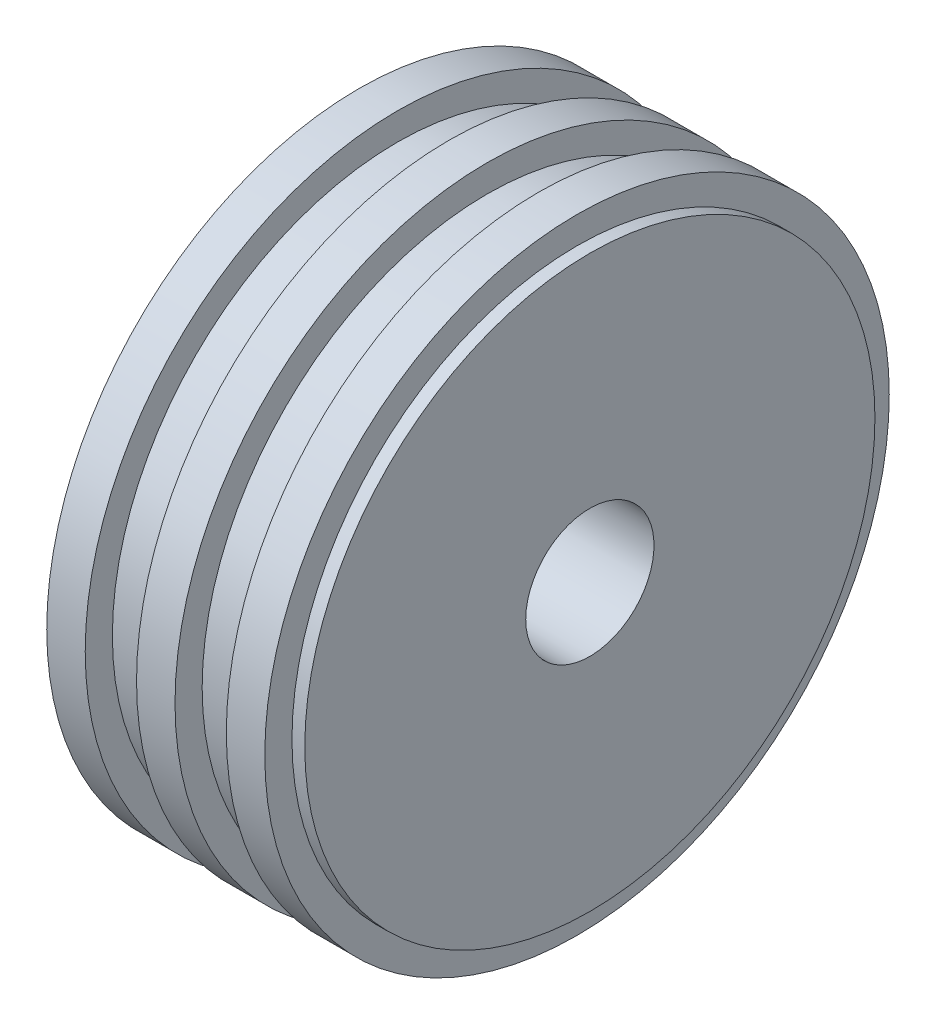
SolidWorks part; units mm, degrees
ref_plane "Front Plane" through (0, 0, 0) normal (0, 0, 1) x (1, 0, 0)
ref_plane "Top Plane" through (0, 0, 0) normal (0, 1, 0) x (1, 0, 0)
ref_plane "Right Plane" through (0, 0, 0) normal (1, 0, 0) x (0, 0, -1)
sketch "Sketch1" plane through (0, 0, 0) normal (0, 0, 1) x (1, 0, 0)
  line L0 (0, 0) -> (35406.0284, 0) construction
  line L1 (0, 0) -> (0, -35406.0284) construction
  line L2 (-28.5, 0) -> (-28.5, 66.675)
  line L3 (-28.5, 66.675) -> (-25.5, 66.675)
  line L4 (-25.5, 66.675) -> (-25.5, 73.025)
  line L5 (-25.5, 73.025) -> (-16.5, 73.025)
  line L6 (-16.5, 73.025) -> (-16.5, 66.675)
  line L7 (-16.5, 66.675) -> (-4.5, 66.675)
  line L8 (-4.5, 66.675) -> (-4.5, 73.025)
  line L9 (-4.5, 73.025) -> (4.5, 73.025)
  line L10 (4.5, 73.025) -> (4.5, 66.675)
  line L11 (4.5, 66.675) -> (16.5, 66.675)
  line L12 (16.5, 66.675) -> (16.5, 73.025)
  line L13 (16.5, 73.025) -> (25.5, 73.025)
  line L14 (25.5, 73.025) -> (25.5, 66.675)
  line L15 (25.5, 66.675) -> (28.5, 66.675)
  line L16 (28.5, 66.675) -> (28.5, 0)
  line L17 (-28.5, 0) -> (28.5, 0)
  dimension "D1" = 57
  dimension "D2" = 146.05
  dimension "D3" = 133.35
  dimension "D4" = 3
  dimension "D5" = 9
  dimension "D6" = 12
revolve "Revolve1" add sketch "Sketch1" angle 360 about L0
sketch "Sketch2" plane through (-28.5, 0, 0) normal (-1, 0, 0) x (0, 0, 1)
  circle A0 centre (0, 0) radius 15
  dimension "D1" = 30
extrude "Cut-Extrude1" cut sketch "Sketch2" against normal through all
